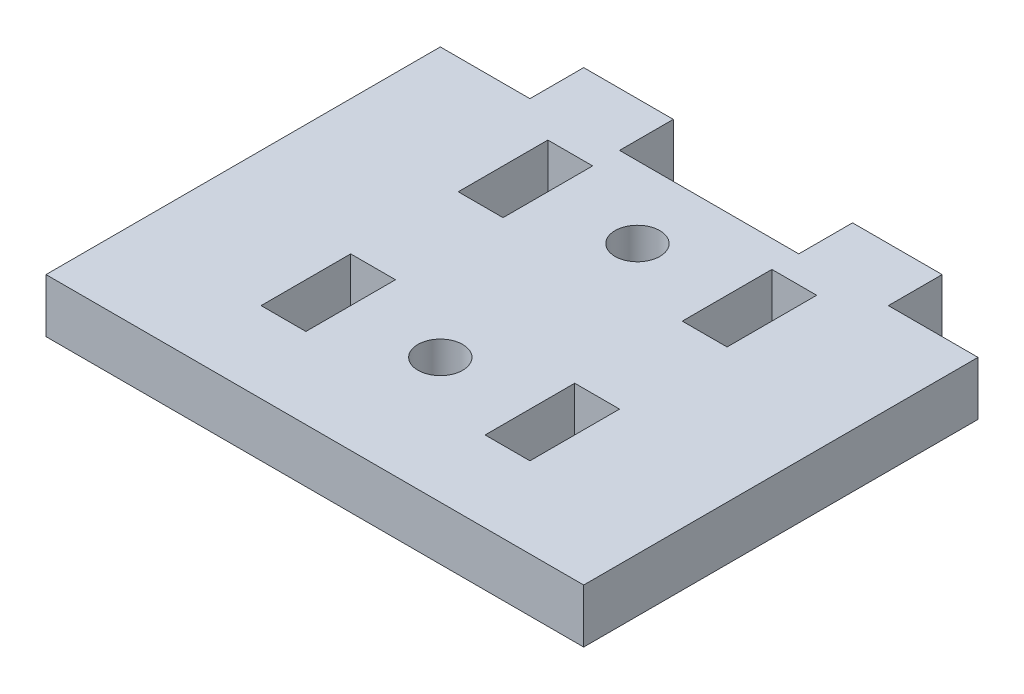
SolidWorks part; units mm, degrees
ref_plane "Front Plane" through (0, 0, 0) normal (0, 0, 1) x (1, 0, 0)
ref_plane "Top Plane" through (0, 0, 0) normal (0, 1, 0) x (1, 0, 0)
ref_plane "Right Plane" through (0, 0, 0) normal (1, 0, 0) x (0, 0, -1)
sketch "Sketch2" plane through (0, 0, 0) normal (0, 1, 0) x (1, 0, 0)
  line L0 (-12.9238, 0.285) -> (-7.9238, 0.285)
  line L1 (-27.9238, 25.285) -> (-17.9238, 25.285)
  line L2 (-27.9238, 25.285) -> (-27.9238, -18.715)
  line L3 (-27.9238, -18.715) -> (32.0762, -18.715)
  line L4 (32.0762, 25.285) -> (32.0762, -18.715)
  line L6 (-17.9238, 25.285) -> (-17.9238, 31.285)
  line L7 (-17.9238, 31.285) -> (-7.9238, 31.285)
  line L8 (-7.9238, 25.285) -> (-7.9238, 31.285)
  line L10 (12.0762, 25.285) -> (12.0762, 31.285)
  line L11 (12.0762, 31.285) -> (22.0762, 31.285)
  line L12 (22.0762, 25.285) -> (22.0762, 31.285)
  line L13 (-12.9238, 22.285) -> (-7.9238, 22.285)
  line L14 (-12.9238, 22.285) -> (-12.9238, 12.285)
  line L15 (-12.9238, 12.285) -> (-7.9238, 12.285)
  line L16 (-7.9238, 22.285) -> (-7.9238, 12.285)
  line L17 (-12.9238, 0.285) -> (-12.9238, -9.715)
  line L18 (-12.9238, -9.715) -> (-7.9238, -9.715)
  line L19 (-7.9238, 0.285) -> (-7.9238, -9.715)
  line L20 (12.0762, 22.285) -> (17.0762, 22.285)
  line L21 (12.0762, 22.285) -> (12.0762, 12.285)
  line L22 (12.0762, 12.285) -> (17.0762, 12.285)
  line L23 (17.0762, 22.285) -> (17.0762, 12.285)
  line L24 (12.0762, 0.285) -> (17.0762, 0.285)
  line L25 (12.0762, 0.285) -> (12.0762, -9.715)
  line L26 (12.0762, -9.715) -> (17.0762, -9.715)
  line L27 (17.0762, 0.285) -> (17.0762, -9.715)
  line L28 (-7.9238, 25.285) -> (12.0762, 25.285)
  line L29 (22.0762, 25.285) -> (32.0762, 25.285)
  circle A0 centre (2.0762, 17.285) radius 2.5
  circle A1 centre (2.0762, -4.715) radius 2.5
  point P32 (4.4275, 14.147)
  point P33 (4.4275, -3.1785)
  point P34 (0, 0)
  point P35 (0, 0)
  dimension "D1" = 6
  dimension "D7" = 5
  dimension "D2" = 10
  dimension "D3" = 6
  dimension "D4" = 10
  dimension "D5" = 60
  dimension "D6" = 50
  dimension "D8" = 10
  dimension "D9" = 5
  dimension "D10" = 10
  dimension "D11" = 5
  dimension "D12" = 10
  dimension "D13" = 5
  dimension "D14" = 5
  dimension "D15" = 10
  dimension "D16" = 9
  dimension "D17" = 9
  dimension "D18" = 15
  dimension "D19" = 15
  dimension "D20" = 15
  dimension "D21" = 15
  dimension "D22" = 10
  dimension "D23" = 10
  dimension "D24" = 9
  dimension "D25" = 9
  dimension "D26" = 5
  dimension "D27" = 10
  dimension "D28" = 10
extrude "Boss-Extrude1" add sketch "Sketch2" along normal blind 6
